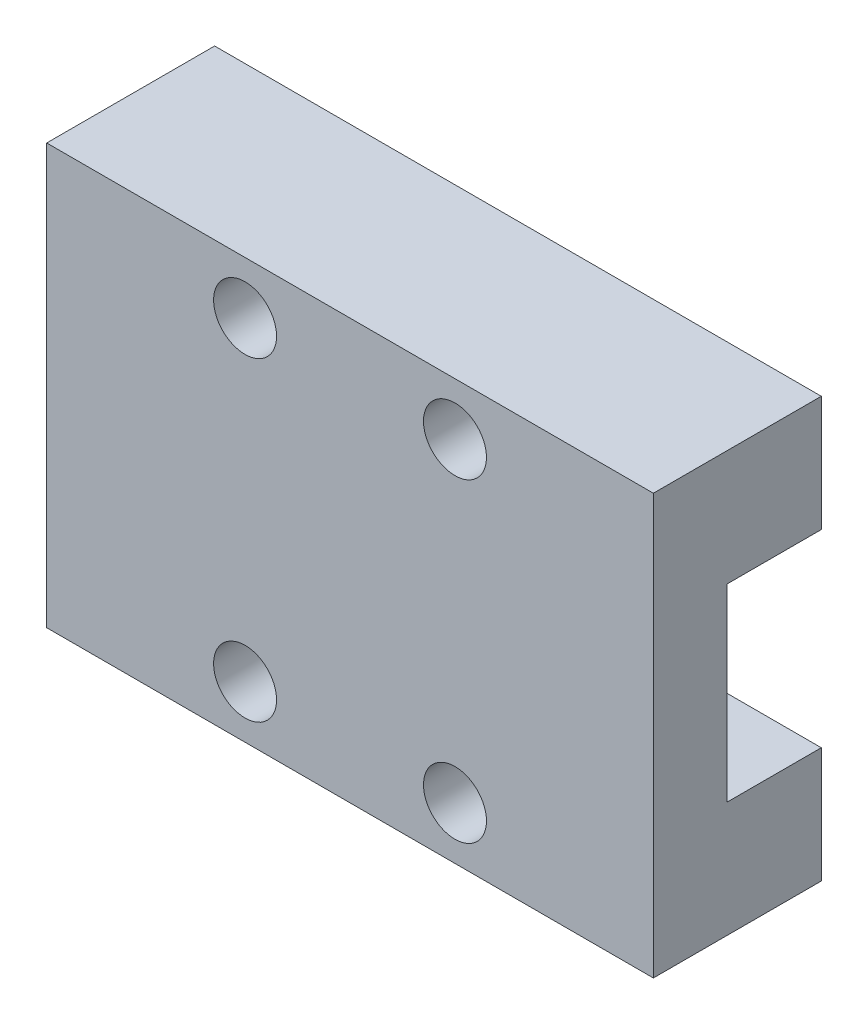
SolidWorks part; units mm, degrees
ref_plane "前视基准面" through (0, 0, 0) normal (0, 0, 1) x (1, 0, 0)
ref_plane "上视基准面" through (0, 0, 0) normal (0, 1, 0) x (1, 0, 0)
ref_plane "右视基准面" through (0, 0, 0) normal (1, 0, 0) x (0, 0, -1)
sketch "草图1" plane through (0, 0, 0) normal (0, 0, 1) x (1, 0, 0)
  line L0 (0, 0) -> (30.0712, 0) construction
  line L1 (0, 0) -> (0, 19.2472) construction
  line L3 (14.45, -10) -> (-14.45, -10)
  line L4 (14.45, -10) -> (14.45, 10)
  line L5 (14.45, 10) -> (-14.45, 10)
  line L6 (-14.45, -10) -> (-14.45, 10)
  line L7 (14.45, -10) -> (-14.45, 10) construction
  line L8 (14.45, 10) -> (-14.45, -10) construction
  point P1 (0, 0)
  dimension "D1" = 28.9
  dimension "D2" = 20
extrude "凸台-拉伸1" add sketch "草图1" along normal blind 8
sketch "草图2" plane through (0, 0, 0) normal (0, 0, -1) x (-1, 0, 0)
  line L0 (-14.45, -10) -> (-14.45, 10) construction
  line L1 (14.45, -4.5) -> (-14.45, -4.5)
  line L2 (14.45, -4.5) -> (14.45, 4.5)
  line L3 (14.45, 4.5) -> (-14.45, 4.5)
  line L4 (-14.45, -4.5) -> (-14.45, 4.5)
  line L5 (14.45, -4.5) -> (-14.45, 4.5) construction
  line L6 (14.45, 4.5) -> (-14.45, -4.5) construction
  line L7 (-14.45, 10) -> (14.45, 10) construction
  point P0 (0, 0)
  dimension "D1" = 5.5
extrude "切除-拉伸1" cut sketch "草图2" against normal blind 4.5
sketch "草图3" plane through (0, 0, 8) normal (0, 0, 1) x (1, 0, 0)
  line L0 (0, 0) -> (23.6472, 0) construction
  line L1 (0, 0) -> (0, 14.3598) construction
  circle A0 centre (-5, 7.5) radius 1.5
  circle A1 centre (-5, -7.5) radius 1.5
  circle A2 centre (5, 7.5) radius 1.5
  circle A3 centre (5, -7.5) radius 1.5
  dimension "D1" = 3
  dimension "D2" = 10
  dimension "D3" = 15
extrude "切除-拉伸2" cut sketch "草图3" against normal blind 3
sketch "草图6" plane through (0, 0, 8) normal (0, 0, 1) x (1, 0, 0)
  line L0 (-14.45, -10) -> (14.45, -10) construction
  line L1 (-14.45, 10) -> (-8.45, 10)
  line L2 (-14.45, 10) -> (-14.45, -10)
  line L3 (-14.45, -10) -> (-8.45, -10)
  line L4 (-8.45, 10) -> (-8.45, -10)
  line L5 (0, 0) -> (0, 11.6603) construction
  line L6 (14.45, -10) -> (8.45, -10)
  line L7 (8.45, 10) -> (8.45, -10)
  line L8 (14.45, 10) -> (8.45, 10)
  line L9 (14.45, 10) -> (14.45, -10)
  dimension "D1" = 6
